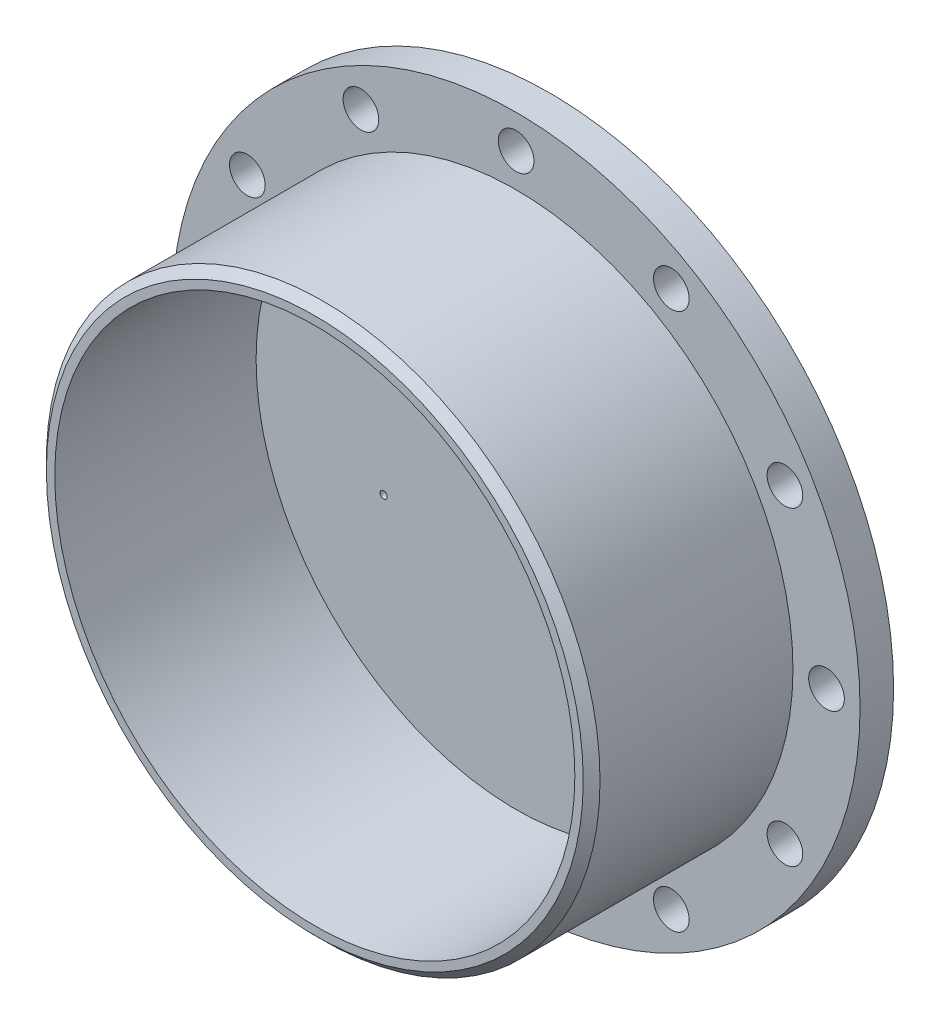
SolidWorks part; units mm, degrees
ref_plane "Front Plane" through (0, 0, 0) normal (0, 0, 1) x (1, 0, 0)
ref_plane "Top Plane" through (0, 0, 0) normal (0, 1, 0) x (1, 0, 0)
ref_plane "Right Plane" through (0, 0, 0) normal (1, 0, 0) x (0, 0, -1)
sketch "Sketch1" plane through (0, 0, 0) normal (0, 0, 1) x (1, 0, 0)
  circle A1 centre (0, 0) radius 130.175
  circle A2 centre (0, 0) radius 104.775
  point P55 (0, 0)
extrude "Boss-Extrude1" add sketch "Sketch1" along normal blind 6.35
sketch "Sketch2" plane through (0, 0, 0) normal (0, 0, 1) x (1, 0, 0)
  circle A0 centre (0, 0) radius 98.425
  circle A1 centre (0, 0) radius 104.775
extrude "Boss-Extrude2" add sketch "Sketch2" along normal blind 82.55
sketch "Sketch3" plane through (0, 0, 0) normal (0, 0, -1) x (-1, 0, 0)
  circle A0 centre (0, 0) radius 98.425
  dimension "D1" = 196.85
extrude "Boss-Extrude3" add sketch "Sketch3" against normal blind 6.35
chamfer "Chamfer1" distance 3.175 1 edges at (104.775, 0, 82.55)
hole_wizard "1/2 Clearance Hole1" positions "Sketch4" profile "Sketch5" hole size "1/2" standard "ANSI Inch" end condition through all
sketch "Sketch4" plane through (0, 0, 6.35) normal (0, 0, 1) x (1, 0, 0)
  point P0 (0, 117.475)
  dimension "D1" = 117.475
sketch "Sketch5" plane through (0, 117.475, 6.35) normal (1, 0, 0) x (0, -1, 0)
  line L0 (0, 0) -> (0, 6.35)
  line L1 (0, 6.35) -> (6.7462, 6.35)
  line L2 (6.7462, 6.35) -> (6.7462, 0)
  line L5 (6.7462, 0) -> (0, 0)
  line L11 (0, -6.35) -> (0, 107.95) construction
  dimension "Thru Hole Dia." = 13.4925
  dimension "Thru Hole Depth" = 6.35
pattern_circular "CirPattern1" count 12 over 360 about axis through (0, 0, 0) along (0, 0, 1) of "1/2 Clearance Hole1"
sketch "Sketch6" plane through (0, 0, 6.35) normal (0, 0, 1) x (1, 0, 0)
  line L0 (-50.165, 20.32) -> (21.59, 20.32)
  line L1 (50.165, -31.75) -> (21.59, -31.75)
  line L2 (50.165, -31.75) -> (50.165, 31.75)
  line L3 (50.165, 31.75) -> (21.59, 31.75)
  line L4 (-50.165, -20.32) -> (-50.165, 20.32)
  line L5 (21.59, 20.32) -> (21.59, 31.75)
  line L6 (-50.165, -20.32) -> (21.59, -20.32)
  line L7 (21.59, -20.32) -> (21.59, -31.75)
  line L8 (-50.165, 0) -> (50.165, 0)
  line L9 (21.59, 20.32) -> (21.59, -20.32)
  point P0 (50.165, 0)
  point P5 (0, 0)
  point P14 (-50.165, 0)
  dimension "D1" = 40.64
  dimension "D2" = 63.5
  dimension "D3" = 100.33
  dimension "D4" = 21.59
other "Move Face1" face at (65.4837, 101.7363, 0) parameters "D1"=6.35
hole_wizard "Tap Drill for #6-32 Tap1" positions "3DSketch1" profile "Sketch10" hole size "#6-32" standard "ANSI Inch"
sketch3d "3DSketch1"
  point P0 (-50.165, 20.32, 6.35)
  point P3 (-50.165, -20.32, 6.35)
  point P6 (50.165, -31.75, 6.35)
  point P9 (50.165, 31.75, 6.35)
sketch "Sketch10" plane through (-50.165, 20.32, 6.35) normal (1, 0, 0) x (0, -1, 0)
  line L0 (0, 0) -> (0, 7.1627)
  line L1 (0, 7.1627) -> (1.3525, 6.35)
  line L2 (1.3525, 6.35) -> (1.3525, 0)
  line L5 (1.3525, 0) -> (0, 0)
  line L10 (0, 7.1627) -> (-1.3526, 6.35) construction
  line L11 (0, -6.35) -> (0, 107.95) construction
  dimension "Hole Dia." = 2.7051
  dimension "Hole Depth" = 6.35
  dimension "Drill Angle" = 118
